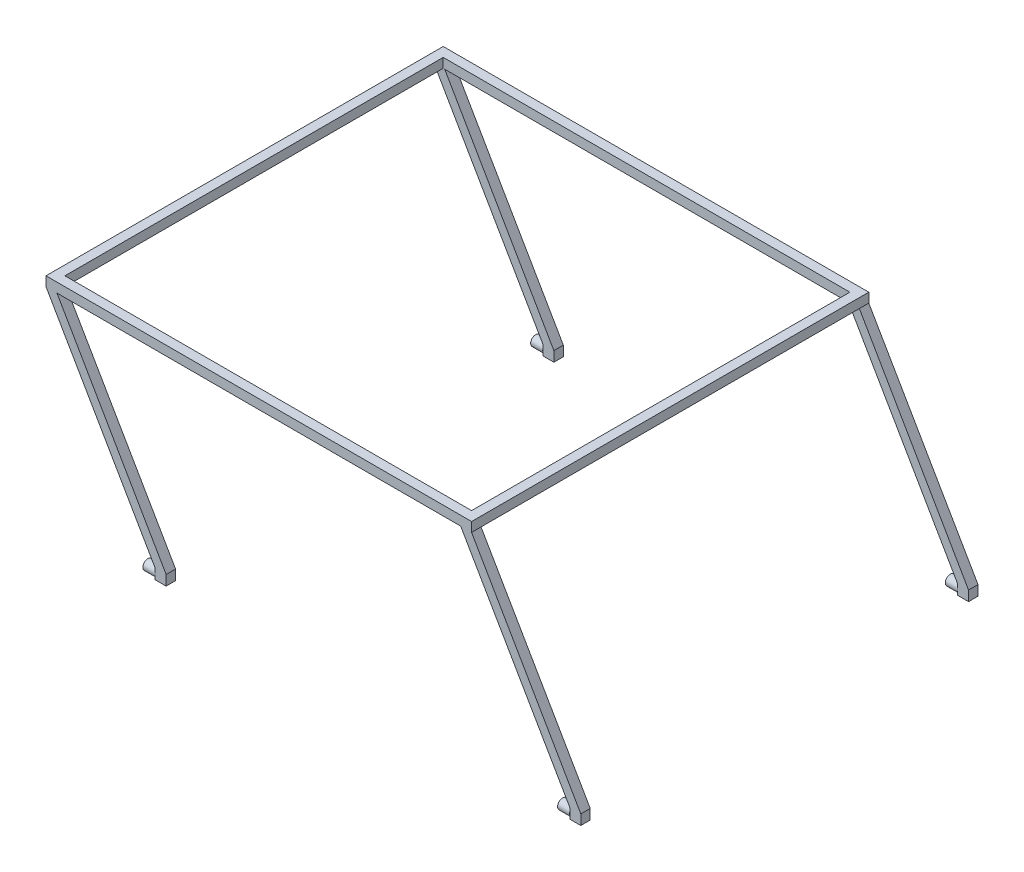
SolidWorks part; units mm, degrees
ref_plane "Front Plane" through (0, 0, 0) normal (0, 0, 1) x (1, 0, 0)
ref_plane "Top Plane" through (0, 0, 0) normal (0, 1, 0) x (1, 0, 0)
ref_plane "Right Plane" through (0, 0, 0) normal (1, 0, 0) x (0, 0, -1)
sketch "Sketch1" plane through (0, 0, 0) normal (0, 1, 0) x (1, 0, 0)
  line L1 (-225, 210) -> (225, 210)
  line L2 (-225, 210) -> (-225, -210)
  line L3 (-225, -210) -> (225, -210)
  line L4 (225, 210) -> (225, -210)
  line L5 (-225, 210) -> (225, -210) construction
  line L6 (-225, -210) -> (225, 210) construction
  line L7 (-215, -200) -> (215, -200)
  line L8 (-215, -200) -> (-215, 200)
  line L9 (-215, 200) -> (215, 200)
  line L10 (215, -200) -> (215, 200)
  point P0 (0, 0)
  dimension "D1" = 420
  dimension "D2" = 450
  dimension "D3" = 10
  dimension "D4" = 10
  dimension "D5" = 10
  dimension "D6" = 10
extrude "Boss-Extrude1" add sketch "Sketch1" along normal blind 10
ref_plane "Plane1" through (0, -200, 0) normal (0, 1, 0) x (1, 0, 0)
sketch "Sketch4" plane through (0, 0, 210) normal (0, 0, 1) x (1, 0, 0)
  line L0 (-225, 0) -> (-109.5299, -200)
  line L1 (-213.453, 0) -> (-97.9829, -200)
  line L2 (-225, 0) -> (225, 0) construction
  line L4 (231, -200) -> (-231, -200) construction
  line L5 (-109.5299, -200) -> (-97.9829, -200)
  line L6 (-225, 0) -> (-213.453, 0)
  line L7 (225, 0) -> (340.4701, -200)
  line L8 (340.4701, -200) -> (328.923, -200)
  line L9 (328.923, -200) -> (213.453, 0)
  line L10 (213.453, 0) -> (225, 0)
  dimension "D1" = 10
  dimension "D2" = 60
  dimension "D3" = 10
  dimension "D4" = 60
  dimension "D5" = 0
extrude "Boss-Extrude2" add sketch "Sketch4" against normal blind 10
mirror "Mirror1" about plane through (0, 0, 0) normal (0, 0, 1) of "Boss-Extrude2"
sketch "Sketch8" plane through (0, -200, 0) normal (0, -1, 0) x (1, 0, 0)
  line L1 (-109.5299, 210) -> (-97.9829, 210)
  line L2 (-109.5299, 210) -> (-109.5299, 200)
  line L3 (-109.5299, 200) -> (-97.9829, 200)
  line L4 (-97.9829, 210) -> (-97.9829, 200)
  line L5 (340.4701, 210) -> (328.923, 210)
  line L6 (340.4701, 210) -> (340.4701, 200)
  line L7 (340.4701, 200) -> (328.923, 200)
  line L8 (328.923, 210) -> (328.923, 200)
extrude "Boss-Extrude3" add sketch "Sketch8" along normal blind 10.67
mirror "Mirror2" about plane through (0, 0, 0) normal (0, 0, 1) of "Boss-Extrude3"
sketch "Sketch9" plane through (-109.5299, 0, 0) normal (-1, 0, 0) x (0, 0, 1)
  line L0 (210, -210.67) -> (200, -210.67) construction
  circle A0 centre (205.0285, -205.335) radius 5.335
  dimension "D1" = 10.67
  dimension "D2" = 5.335
extrude "Boss-Extrude4" add sketch "Sketch9" along normal blind 12.7
sketch "Sketch10" plane through (328.923, 0, 0) normal (-1, 0, 0) x (0, 0, 1)
  circle A0 centre (205, -205.335) radius 5.335
extrude "Boss-Extrude5" add sketch "Sketch10" along normal blind 12.7
mirror "Mirror3" about plane through (0, 0, 0) normal (0, 0, 1) of "Boss-Extrude4", "Boss-Extrude5"
